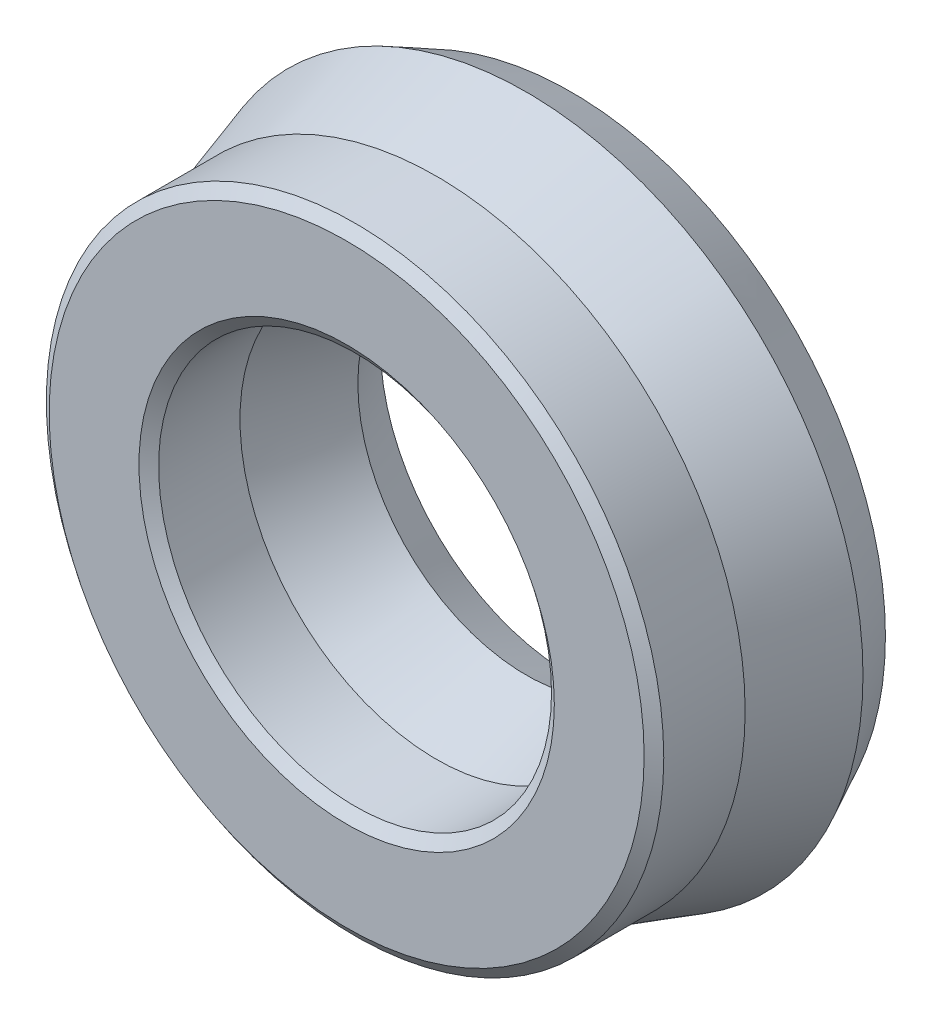
SolidWorks part; units mm, degrees
ref_plane "Front Plane" through (0, 0, 0) normal (0, 0, 1) x (1, 0, 0)
ref_plane "Top Plane" through (0, 0, 0) normal (0, 1, 0) x (1, 0, 0)
ref_plane "Right Plane" through (0, 0, 0) normal (1, 0, 0) x (0, 0, -1)
sketch "Sketch2" plane through (0, 0, 0) normal (1, 0, 0) x (0, 0, -1)
  line L10 (-17.3134, 4.9554) -> (14.643, 4.9554) construction
  line L11 (0.0247, 1.5554) -> (0.0247, 1.0554)
  line L12 (0.0247, 1.5554) -> (-0.7755, 1.9551)
  line L13 (0.0247, -0.6446) -> (-0.7753, -1.0446)
  line L14 (-0.7753, -1.0446) -> (-2.3753, -0.545)
  line L15 (-2.3753, -0.545) -> (-3.8253, -0.545)
  line L16 (-3.8253, -0.545) -> (-3.9753, -0.345)
  line L17 (-3.9753, -0.345) -> (-3.9753, 1.255)
  line L18 (-3.9753, 1.255) -> (-3.8253, 1.455)
  line L19 (-3.8253, 1.455) -> (-2.3753, 1.455)
  line L20 (-2.3753, 1.455) -> (-0.7755, 1.9551)
  line L21 (-3.9753, 0.455) -> (-0.2692, 0.455) construction
  line L24 (0.0247, -0.1453) -> (0.0247, -0.6446)
  line L27 (0.0247, -0.1453) -> (-1.3413, 0.3117)
  line L28 (-1.3413, 0.5984) -> (0.0247, 1.0554)
  arc A0 (-1.3413, 0.5984) -> (-1.3413, 0.3117) centre (-1.2802, 0.455) ccw
  point P0 (0.0247, 1.5554)
  point P1 (0.0247, -0.6446)
  point P2 (0.0247, 1.0554)
  point P4 (0.0247, -0.1453)
  dimension "D11" = 0.2
  dimension "D2" = 2.9997
  dimension "D3" = 2.2
  dimension "D4" = 2
  dimension "D5" = 0.15
  dimension "D6" = 1.6
  dimension "D7" = 4
  dimension "D8" = 1.6
  dimension "D9" = 0.4
  dimension "D10" = 0.5
  dimension "D12" = 0.15
  dimension "D13" = 108.5
  dimension "D14" = 6
revolve "Revolve1" add sketch "Sketch2" angle 360 about L10
